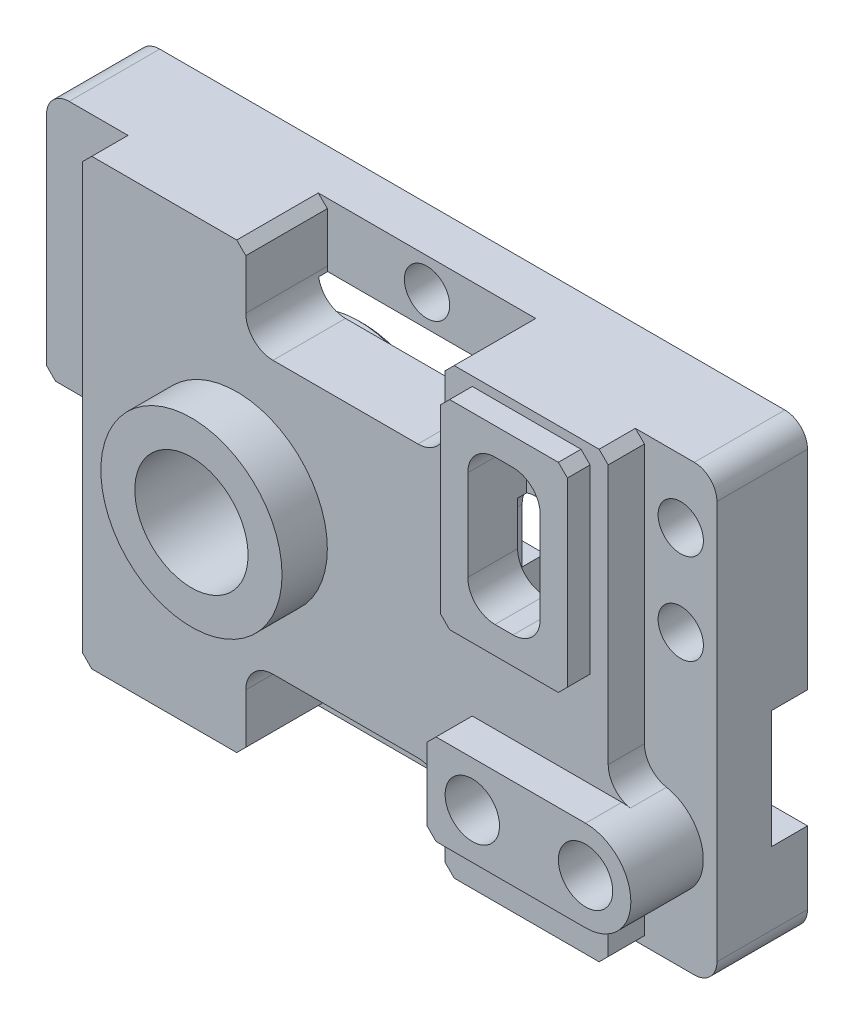
SolidWorks part; units mm, degrees
ref_plane "前视基准面" through (0, 0, 0) normal (0, 0, 1) x (1, 0, 0)
ref_plane "上视基准面" through (0, 0, 0) normal (0, 1, 0) x (1, 0, 0)
ref_plane "右视基准面" through (0, 0, 0) normal (1, 0, 0) x (0, 0, -1)
sketch "草图1" plane through (0, 0, 0) normal (0, 0, 1) x (1, 0, 0)
  line L0 (0, 0) -> (0, 49) construction
  line L1 (-74, 49) -> (74, 49)
  line L2 (-74, 49) -> (-74, -49)
  line L3 (-74, -49) -> (74, -49)
  line L4 (74, 49) -> (74, -49)
  line L5 (0, 0) -> (74, 0) construction
  dimension "D1" = 148
  dimension "D2" = 98
extrude "凸台-拉伸1" add sketch "草图1" along normal blind 28 contours L3 L4 L1 L2
fillet "圆角1" radius 5 4 edges at (-74, 49, 14) (-74, -49, 14) (74, 49, 14) (74, -49, 14)
sketch "草图2" plane through (0, 0, 28) normal (0, 0, 1) x (1, 0, 0)
  line L1 (-58, 49) -> (58, 49)
  line L2 (-58, 49) -> (-58, -49)
  line L3 (-58, -49) -> (58, -49)
  line L4 (58, 49) -> (58, -49)
  line L5 (0, 0) -> (0, 49) construction
  line L6 (0, 0) -> (58, 0) construction
  dimension "D1" = 116
  dimension "D2" = 98
sketch "草图3" plane through (0, 0, 0) normal (0, 0, -1) x (-1, 0, 0)
  line L0 (74, 44) -> (74, -44) construction
  line L1 (-55, -35) -> (55, -35)
  line L2 (-55, -35) -> (-55, 35)
  line L3 (-55, 35) -> (55, 35)
  line L4 (55, -35) -> (55, 35)
  line L5 (-55, -35) -> (55, 35) construction
  line L6 (-55, 35) -> (55, -35) construction
  line L7 (55, 35) -> (58, 35)
  line L8 (55, 35) -> (55, -5)
  line L9 (55, -5) -> (58, -5)
  line L10 (64, 29) -> (64, 1)
  line L11 (-55, -35) -> (-58, -35)
  line L12 (-55, -35) -> (-55, 5)
  line L13 (-55, 5) -> (-58, 5)
  line L14 (-64, -29) -> (-64, -1)
  line L15 (-74, 44) -> (-74, -44) construction
  arc A0 (-58, 5) -> (-64, -1) centre (-58, -1) ccw
  arc A1 (-58, -35) -> (-64, -29) centre (-58, -29) cw
  arc A2 (58, 35) -> (64, 29) centre (58, 29) cw
  arc A3 (64, 1) -> (58, -5) centre (58, 1) cw
  point P0 (0, 0)
  dimension "D5" = 6
  dimension "D6" = 6
  dimension "D1" = 110
  dimension "D2" = 70
  dimension "D3" = 10
  dimension "D4" = 10
  dimension "D7" = 40
  dimension "D8" = 40
extrude "切除-拉伸1" cut sketch "草图3" against normal blind 12 contours A1 L11 L2 L13 A0 L14 | L1 L4 L3 L2 | A3 L10 A2 L7 L4 L9
fillet "圆角2" radius 6 2 edges at (-55, -35, 6) (55, 35, 6)
sketch "草图4" plane through (0, 0, 12) normal (0, 0, -1) x (-1, 0, 0)
  line L0 (0, 0) -> (-58, 0) construction
  line L1 (-46, -25) -> (-13, -25)
  line L2 (-52, -19) -> (-52, 19)
  line L3 (-46, 25) -> (-13, 25)
  line L4 (-7, -19) -> (-7, 19)
  line L5 (-52, -25) -> (-7, 25) construction
  line L6 (-52, 25) -> (-7, -25) construction
  line L7 (0, 0) -> (0, 49) construction
  arc A0 (-52, -19) -> (-46, -25) centre (-46, -19) ccw
  arc A1 (-13, -25) -> (-7, -19) centre (-13, -19) ccw
  arc A2 (-7, 19) -> (-13, 25) centre (-13, 19) ccw
  arc A3 (-46, 25) -> (-52, 19) centre (-46, 19) ccw
  point P0 (-29.5, 0)
  dimension "D4" = 6
  dimension "D1" = 50
  dimension "D2" = 45
  dimension "D3" = 7
extrude "切除-拉伸2" cut sketch "草图4" against normal blind 5
sketch "草图6" plane through (0, 0, 17) normal (0, 0, -1) x (-1, 0, 0)
  line L4 (-46, -25) -> (-13, -25) construction
  line L5 (-52, 19) -> (-52, -19) construction
  line L6 (-13, 25) -> (-46, 25) construction
  line L7 (-46, -25) -> (-34, -25)
  line L8 (-52, 19) -> (-52, -19)
  line L9 (-34, 25) -> (-46, 25)
  line L10 (-28, 19) -> (-28, -19)
  arc A4 (-52, -19) -> (-46, -25) centre (-46, -19) ccw construction
  arc A5 (-46, 25) -> (-52, 19) centre (-46, 19) ccw construction
  arc A6 (-52, -19) -> (-46, -25) centre (-46, -19) ccw
  arc A7 (-46, 25) -> (-52, 19) centre (-46, 19) ccw
  arc A8 (-34, -25) -> (-28, -19) centre (-34, -19) ccw
  arc A9 (-28, 19) -> (-34, 25) centre (-34, 19) ccw
  dimension "D1" = 6
  dimension "D2" = 24
extrude "切除-拉伸3" cut sketch "草图6" against normal blind 5
sketch "草图7" plane through (0, 0, 17) normal (0, 0, -1) x (-1, 0, 0)
  line L0 (-28, -19) -> (-28, 19) construction
  line L1 (-28, 7) -> (-21, 7)
  line L2 (-28, 7) -> (-28, -7)
  line L3 (-28, -7) -> (-21, -7)
  line L4 (-21, 7) -> (-21, -7)
  line L6 (0, 0) -> (20.0971, 0) construction
  dimension "D1" = 7
  dimension "D2" = 14
extrude "凸台-拉伸2" add sketch "草图7" along normal blind 5
sketch "草图8" plane through (0, 0, 12) normal (0, 0, -1) x (-1, 0, 0)
  line L0 (0, 0) -> (31.959, 0) construction
  line L1 (0, 0) -> (0, 23.298) construction
  circle A0 centre (24, 0) radius 20
  dimension "D1" = 40
  dimension "D2" = 24
extrude "凸台-拉伸3" add sketch "草图8" along normal blind 12
sketch "草图9" plane through (0, 0, 0) normal (0, 0, -1) x (-1, 0, 0)
  circle A3 centre (24, 0) radius 15
  dimension "D2" = 30
extrude "切除-拉伸4" cut sketch "草图9" against normal blind 20
sketch "草图10" plane through (0, 0, 0) normal (0, 0, -1) x (-1, 0, 0)
  line L0 (-74, 44) -> (-74, -44) construction
  line L1 (-74, -2) -> (-64, -2)
  line L2 (-74, -2) -> (-74, -28)
  line L3 (-74, -28) -> (-64, -28)
  line L4 (-64, -2) -> (-64, -28)
  line L5 (-64, -29) -> (-64, -1) construction
  line L6 (64, 29) -> (64, 1) construction
  line L7 (64, 28) -> (74, 28)
  line L8 (64, 28) -> (64, 2)
  line L9 (64, 2) -> (74, 2)
  line L10 (74, 28) -> (74, 2)
  line L11 (74, 44) -> (74, -44) construction
  line L12 (0, 0) -> (28.5525, 0) construction
  line L13 (0, 0) -> (-58, 0) construction
  dimension "D1" = 2
  dimension "D2" = 2
  dimension "D3" = 26
  dimension "D4" = 26
extrude "切除-拉伸5" cut sketch "草图10" against normal blind 8
sketch "草图12" plane through (0, 0, 28) normal (0, 0, 1) x (1, 0, 0)
  line L1 (0, 0) -> (0, -58.7728) construction
  line L2 (-69, -49) -> (69, -49) construction
  line L3 (22, -49) -> (-22, -49)
  line L4 (22, -49) -> (22, -36)
  line L5 (16, -30) -> (-16, -30)
  line L6 (-22, -49) -> (-22, -36)
  line L7 (0, 0) -> (40.7358, 0) construction
  line L8 (-22, 49) -> (-22, 36)
  line L9 (16, 30) -> (-16, 30)
  line L10 (22, 49) -> (22, 36)
  line L11 (22, 49) -> (-22, 49)
  arc A0 (22, 36) -> (16, 30) centre (16, 36) cw
  arc A1 (-16, 30) -> (-22, 36) centre (-16, 36) cw
  arc A2 (22, -36) -> (16, -30) centre (16, -36) ccw
  arc A3 (-16, -30) -> (-22, -36) centre (-16, -36) ccw
  point P19 (22, 30)
  point P22 (-22, 30)
  point P25 (22, -30)
  point P28 (-22, -30)
  dimension "D3" = 6
  dimension "D1" = 44
  dimension "D2" = 60
extrude "切除-拉伸6" cut sketch "草图12" against normal blind 18
sketch "草图13" plane through (0, 0, 28) normal (0, 0, 1) x (1, 0, 0)
  line L10 (0, 0) -> (0, -25.7378) construction
  line L16 (0, 0) -> (-29.6884, 0) construction
  line L17 (74, -49) -> (58, -49)
  line L18 (74, -49) -> (74, 49)
  line L19 (74, 49) -> (58, 49)
  line L20 (58, -49) -> (58, -41.7162)
  line L21 (58, -10.2838) -> (58, 49)
  arc A6 (62.875, -35.8226) -> (62.875, -16.1774) centre (61, -26) ccw
  arc A7 (58, -10.2838) -> (62.875, -16.1774) centre (64, -10.2838) ccw
  arc A8 (58, -41.7162) -> (62.875, -35.8226) centre (64, -41.7162) cw
extrude "切除-拉伸7" cut sketch "草图13" against normal blind 8
sketch "草图14" plane through (0, 0, 28) normal (0, 0, 1) x (1, 0, 0)
  line L8 (0, 0) -> (0, 30.3373) construction
  line L9 (-74, 49) -> (-74, -49)
  line L10 (-58, -49) -> (-74, -49)
  line L11 (-58, 49) -> (-58, -49)
  line L12 (-58, 49) -> (-74, 49)
extrude "切除-拉伸8" cut sketch "草图14" against normal blind 8
sketch "草图15" plane through (0, 0, 20) normal (0, 0, 1) x (1, 0, 0)
  line L6 (0, 0) -> (0, 18.4779) construction
  line L7 (0, 0) -> (-27.4729, 0) construction
  line L12 (-58, -49) -> (-74, -49)
  line L13 (-58, -49) -> (-58, -12)
  line L14 (-64, -6) -> (-74, -6)
  line L15 (-74, -49) -> (-74, -6)
  arc A2 (-64, -6) -> (-58, -12) centre (-64, -12) cw
extrude "切除-拉伸9" cut sketch "草图15" against normal blind 8
chamfer "倒角1" distance 2 angle 45 9 edges at (22, 49, 19) (-22, 49, 19) (22, -49, 19) (-22, -49, 19) (-74, -6, 16) (-58, -49, 20) (-58, 49, 24) (58, -49, 24) (58, 49, 24)
sketch "草图17" plane through (0, 0, 28) normal (0, 0, 1) x (1, 0, 0)
  circle A0 centre (-24, 0) radius 20 construction
  circle A1 centre (-24, 0) radius 20
extrude "凸台-拉伸4" add sketch "草图17" along normal blind 10
chamfer "倒角2" distance 1 angle 45 2 edges at (-39, 0, 0) (-44, 0, 0)
sketch "草图18" plane through (0, 0, 38) normal (0, 0, 1) x (1, 0, 0)
  circle A0 centre (-24, 0) radius 12.5
  dimension "D1" = 25
extrude "切除-拉伸10" cut sketch "草图18" against normal through all
sketch "草图19" plane through (0, 0, 28) normal (0, 0, 1) x (1, 0, 0)
  line L0 (40, 3) -> (40, 47) construction
  line L1 (54, 3) -> (26, 3)
  line L2 (54, 3) -> (54, 47)
  line L3 (54, 47) -> (26, 47)
  line L4 (26, 3) -> (26, 47)
  line L5 (0, 0) -> (0, -58.7728) construction
  line L6 (0, 0) -> (40.7358, 0) construction
  dimension "D1" = 44
  dimension "D2" = 28
  dimension "D3" = 40
  dimension "D4" = 3
extrude "凸台-拉伸5" add sketch "草图19" along normal blind 5
sketch "草图20" plane through (0, 0, 33) normal (0, 0, 1) x (1, 0, 0)
  line L0 (40, 47) -> (40, 3) construction
  line L1 (48, 41) -> (32, 41)
  line L2 (48, 41) -> (48, 9)
  line L3 (48, 9) -> (32, 9)
  line L4 (32, 41) -> (32, 9)
  line L5 (48, 41) -> (32, 9) construction
  line L6 (48, 9) -> (32, 41) construction
  line L7 (54, 47) -> (26, 47) construction
  line L8 (26, 3) -> (54, 3) construction
  point P0 (40, 25)
  dimension "D1" = 16
  dimension "D2" = 32
extrude "切除-拉伸11" cut sketch "草图20" against normal blind 13
fillet "圆角3" radius 6 4 edges at (32, 41, 26.5) (48, 41, 26.5) (32, 9, 27.5) (48, 9, 27.5)
chamfer "倒角3" distance 2 angle 45 4 edges at (54, 3, 30.5) (26, 3, 30.5) (54, 47, 30.5) (26, 47, 30.5)
sketch "草图21" plane through (0, 0, 28) normal (0, 0, 1) x (1, 0, 0)
  line L0 (32.4125, -26) -> (61, -26) construction
  line L1 (26, -36) -> (26, -16)
  line L2 (26, -36) -> (61, -36)
  line L3 (-61, 15.4799) -> (-61, 36.5201)
  line L4 (26, -16) -> (61, -16)
  line L5 (61, -36) -> (61, -16) construction
  line L6 (26, -36) -> (61, -16) construction
  line L7 (26, -16) -> (61, -36) construction
  line L21 (56, 49) -> (24, 49)
  line L22 (24, 49) -> (22, 47)
  line L23 (22, 47) -> (22, 36)
  line L24 (16, 30) -> (-16, 30)
  line L25 (-22, 36) -> (-22, 47)
  line L26 (-22, 47) -> (-24, 49)
  line L27 (-24, 49) -> (-56, 49)
  line L28 (-58, 47) -> (-58, -47)
  line L29 (-58, 47) -> (-58, -47)
  line L30 (-58, -47) -> (-56, -49)
  line L31 (-58, -47) -> (-56, -49)
  line L32 (-56, -49) -> (-24, -49)
  line L33 (-24, -49) -> (-22, -47)
  line L34 (-22, -47) -> (-22, -36)
  line L35 (-16, -30) -> (16, -30)
  line L36 (22, -36) -> (22, -47)
  line L37 (22, -47) -> (24, -49)
  line L38 (24, -49) -> (56, -49)
  line L39 (56, -49) -> (58, -47)
  line L40 (56, -49) -> (58, -47)
  line L41 (58, -47) -> (58, -41.7162)
  line L42 (56, 49) -> (24, 49)
  line L43 (24, 49) -> (22, 47)
  line L44 (22, 47) -> (22, 36)
  line L45 (16, 30) -> (-16, 30)
  line L46 (-22, 36) -> (-22, 47)
  line L47 (-22, 47) -> (-24, 49)
  line L48 (-24, 49) -> (-56, 49)
  line L53 (-56, -49) -> (-24, -49)
  line L54 (-24, -49) -> (-22, -47)
  line L55 (-22, -47) -> (-22, -36)
  line L56 (-16, -30) -> (16, -30)
  line L57 (22, -36) -> (22, -47)
  line L58 (22, -47) -> (24, -49)
  line L59 (24, -49) -> (56, -49)
  line L70 (58, -47) -> (58, -41.7162)
  line L71 (58, -10.2838) -> (58, 47)
  line L72 (58, -10.2838) -> (58, 47)
  line L73 (58, 47) -> (56, 49)
  line L74 (58, 47) -> (56, 49)
  line L75 (-56, 49) -> (-58, 47)
  line L76 (-56, 49) -> (-58, 47)
  arc A1 (61, -36) -> (61, -16) centre (61, -26) ccw
  arc A7 (16, 30) -> (22, 36) centre (16, 36) ccw
  arc A8 (-22, 36) -> (-16, 30) centre (-16, 36) ccw
  arc A9 (62.875, -35.8226) -> (58, -41.7162) centre (64, -41.7162) ccw
  arc A10 (62.875, -35.8226) -> (58, -41.7162) centre (64, -41.7162) ccw
  arc A11 (62.875, -35.8226) -> (62.875, -16.1774) centre (61, -26) ccw
  arc A12 (-16, -30) -> (-22, -36) centre (-16, -36) ccw
  arc A13 (22, -36) -> (16, -30) centre (16, -36) ccw
  arc A14 (16, 30) -> (22, 36) centre (16, 36) ccw
  arc A15 (-22, 36) -> (-16, 30) centre (-16, 36) ccw
  arc A19 (-16, -30) -> (-22, -36) centre (-16, -36) ccw
  arc A20 (22, -36) -> (16, -30) centre (16, -36) ccw
  arc A22 (58, -10.2838) -> (62.875, -16.1774) centre (64, -10.2838) ccw
  arc A23 (58, -10.2838) -> (62.875, -16.1774) centre (64, -10.2838) ccw
  point P6 (43.5, -26)
  arc M109 (62.875, -35.8226) -> (62.875, -16.1774) centre (61, -26) ccw
  dimension "D2" = 20
  dimension "D3" = 35
  dimension "D1" = 0
extrude "凸台-拉伸6" add sketch "草图21" along normal blind 8 contours A1 L4 L1 L2 M109
chamfer "倒角4" distance 2 angle 45 2 edges at (26, -36, 32) (26, -16, 32)
sketch "草图22" plane through (0, 0, 0) normal (0, 0, -1) x (-1, 0, 0)
  line L0 (66.1969, -35) -> (66.1969, -15) construction
  line L1 (62.1969, -35) -> (62.1969, -15)
  line L2 (70.1969, -35) -> (70.1969, -15)
  arc A0 (62.1969, -35) -> (70.1969, -35) centre (66.1969, -35) ccw
  arc A1 (70.1969, -15) -> (62.1969, -15) centre (66.1969, -15) ccw
  point P2 (66.1969, -25)
  dimension "D1" = 8
  dimension "D2" = 15
  dimension "D3" = 20
extrude "切除-拉伸12" cut sketch "草图22" against normal through all
sketch "草图23" plane through (0, 0, 0) normal (0, 0, -1) x (-1, 0, 0)
  line L0 (0, 0) -> (0, -58.7728) construction
  line L1 (0, 0) -> (-17.5018, 0) construction
  line L2 (0, 0) -> (-40.7358, 0) construction
  circle A0 centre (0, 42) radius 5
  circle A1 centre (0, -42) radius 5
  dimension "D2" = 10
  dimension "D1" = 84
extrude "切除-拉伸13" cut sketch "草图23" against normal through all contours A1 | A0
sketch "草图24" plane through (0, 0, 36) normal (0, 0, 1) x (1, 0, 0)
  circle A0 centre (61, -26) radius 6
  circle A1 centre (36, -26) radius 6
  dimension "D2" = 12
  dimension "D1" = 25
hole_wizard "Ø12.0 (12) 直径孔1" positions "3D草图1" profile "草图25" hole size "Ø12.0" standard "GB"
sketch3d "3D草图1"
  point P0 (61, -26, 36)
  point P3 (36, -26, 36)
sketch "草图25" plane through (61, -26, 36) normal (1, 0, 0) x (0, -1, 0)
  line L0 (0, 0) -> (0, 13.6052)
  line L1 (0, 13.6052) -> (6, 10)
  line L2 (6, 10) -> (6, 0)
  line L5 (6, 0) -> (0, 0)
  line L10 (0, 13.6052) -> (-6, 10) construction
  line L11 (0, -6.35) -> (0, 107.95) construction
  dimension "孔直径" = 12
  dimension "孔深度" = 10
  dimension "导头角度" = 118
sketch "草图26" plane through (0, 0, 20) normal (0, 0, 1) x (1, 0, 0)
  line L0 (0, 0) -> (40.7358, 0) construction
  circle A0 centre (66.0141, 35) radius 5
  circle A1 centre (66.0141, 15) radius 5
  dimension "D3" = 10
  dimension "D1" = 20
  dimension "D2" = 15
extrude "切除-拉伸14" cut sketch "草图26" against normal through all contours A0 | A1
